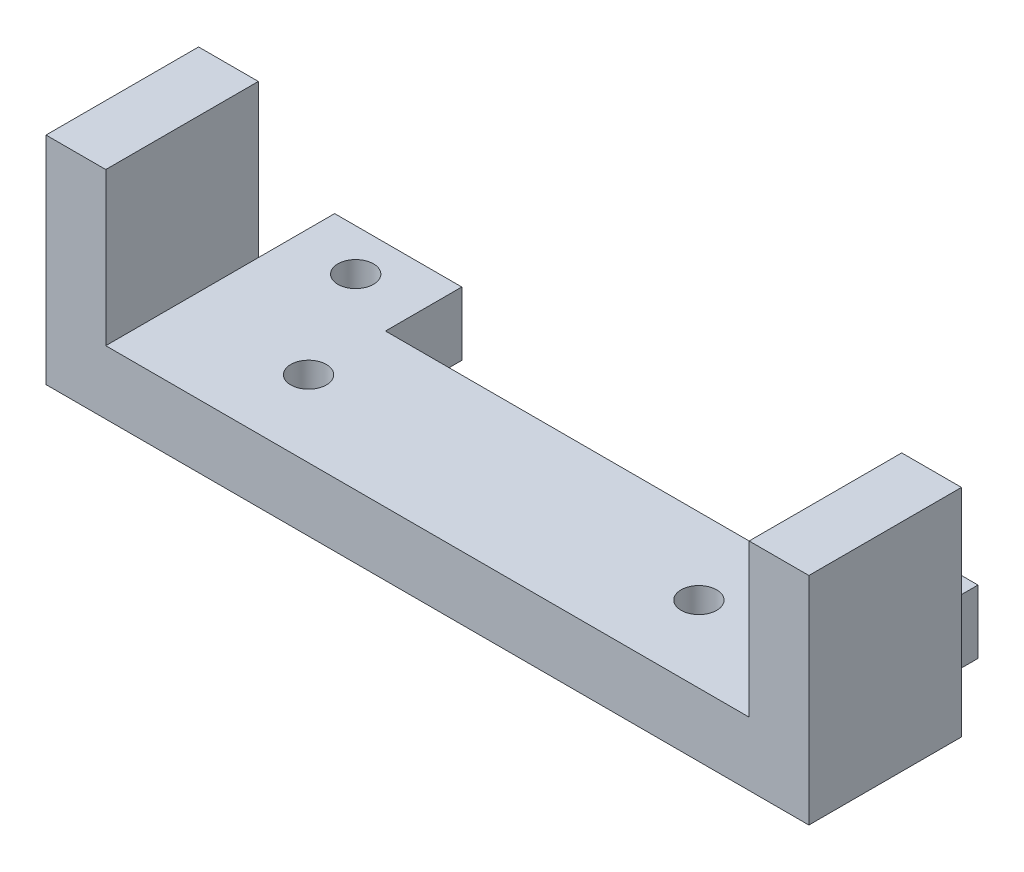
SolidWorks part; units mm, degrees
ref_plane "前视基准面" through (0, 0, 0) normal (0, 0, 1) x (1, 0, 0)
ref_plane "上视基准面" through (0, 0, 0) normal (0, 1, 0) x (1, 0, 0)
ref_plane "右视基准面" through (0, 0, 0) normal (1, 0, 0) x (0, 0, -1)
sketch "草图1" plane through (0, 0, 0) normal (0, 1, 0) x (1, 0, 0)
  line L1 (-30, 6) -> (30, 6)
  line L2 (-30, 6) -> (-30, -6)
  line L3 (-30, -6) -> (30, -6)
  line L4 (30, 6) -> (30, -6)
  dimension "D1" = 60
  dimension "D2" = 30
  dimension "D3" = 12
  dimension "D4" = 6
extrude "凸台-拉伸1" add sketch "草图1" along normal blind 5
sketch "草图2" plane through (0, 5, 0) normal (0, 1, 0) x (1, 0, 0)
  line L0 (-30, -6) -> (30, -6) construction
  line L1 (-30, 6) -> (-25.3, 6)
  line L2 (-30, 6) -> (-30, -6)
  line L3 (-30, -6) -> (-25.3, -6)
  line L4 (-25.3, 6) -> (-25.3, -6)
  line L5 (30, 6) -> (-30, 6) construction
  line L6 (25.3, 6) -> (30, 6)
  line L7 (25.3, 6) -> (25.3, -6)
  line L8 (25.3, -6) -> (30, -6)
  line L9 (30, 6) -> (30, -6)
  dimension "D1" = 4.7
  dimension "D2" = 4.7
extrude "凸台-拉伸2" add sketch "草图2" along normal blind 12
sketch "草图3" plane through (0, 0, 0) normal (0, -1, 0) x (1, 0, 0)
  line L1 (-5, 21) -> (5, 21)
  line L2 (-5, 21) -> (-5, -21)
  line L3 (-5, -21) -> (5, -21)
  line L4 (5, 21) -> (5, -21)
  dimension "D1" = 10
  dimension "D2" = 5
  dimension "D3" = 42
  dimension "D4" = 21
hole_wizard "M3x0.5 螺纹孔3" positions "草图10" profile "草图11" tap size "M3x0.5" standard "JIS" end condition through all
sketch "草图10" plane through (0, 0, 0) normal (0, -1, 0) x (-1, 0, 0)
  point P0 (-15.35, 0)
  point P2 (15.35, 0)
  dimension "D1" = 15.35
  dimension "D2" = 15.35
sketch "草图11" plane through (15.35, 0, 0) normal (1, 0, 0) x (0, 0, -1)
  line L0 (0, 0) -> (0, 17)
  line L1 (0, 17) -> (1.4, 17)
  line L2 (1.4, 17) -> (1.4, 0)
  line L5 (1.4, 0) -> (0, 0)
  line L11 (0, -6.35) -> (0, 107.95) construction
  dimension "通孔螺纹孔钻头直径" = 2.8
  dimension "通孔螺纹孔钻头深度" = 17
cosmetic thread "孔螺纹线7" parameters "D2"=3
cosmetic thread "孔螺纹线8" parameters "D2"=3
sketch "草图12" plane through (0, 5, 0) normal (0, 1, 0) x (1, 0, 0)
  line L1 (-25.3, 6) -> (-15.3, 6)
  line L2 (-25.3, 6) -> (-25.3, 12)
  line L3 (-25.3, 12) -> (-15.3, 12)
  line L4 (-15.3, 6) -> (-15.3, 12)
  line L5 (25.3, 6) -> (15.3, 6)
  line L6 (25.3, 6) -> (25.3, 12)
  line L7 (25.3, 12) -> (15.3, 12)
  line L8 (15.3, 6) -> (15.3, 12)
  dimension "D1" = 10
  dimension "D2" = 10
  dimension "D3" = 6
  dimension "D4" = 6
extrude "凸台-拉伸3" add sketch "草图12" against normal blind 5
hole_wizard "M3x0.5 螺纹孔4" positions "草图13" profile "草图14" tap size "M3x0.5" standard "JIS" end condition through all
sketch "草图13" plane through (0, 0, 0) normal (0, -1, 0) x (-1, 0, 0)
  point P0 (20.35, 8.7066)
  point P2 (-20.35, 8.7066)
  dimension "D1" = 20.35
  dimension "D2" = 20.35
sketch "草图14" plane through (-20.35, 0, -8.7066) normal (1, 0, 0) x (0, 0, -1)
  line L0 (0, 0) -> (0, 17)
  line L1 (0, 17) -> (1.4, 17)
  line L2 (1.4, 17) -> (1.4, 0)
  line L5 (1.4, 0) -> (0, 0)
  line L11 (0, -6.35) -> (0, 107.95) construction
  dimension "通孔螺纹孔钻头直径" = 2.8
  dimension "通孔螺纹孔钻头深度" = 17
cosmetic thread "孔螺纹线9" parameters "D2"=3
cosmetic thread "孔螺纹线10" parameters "D2"=3
